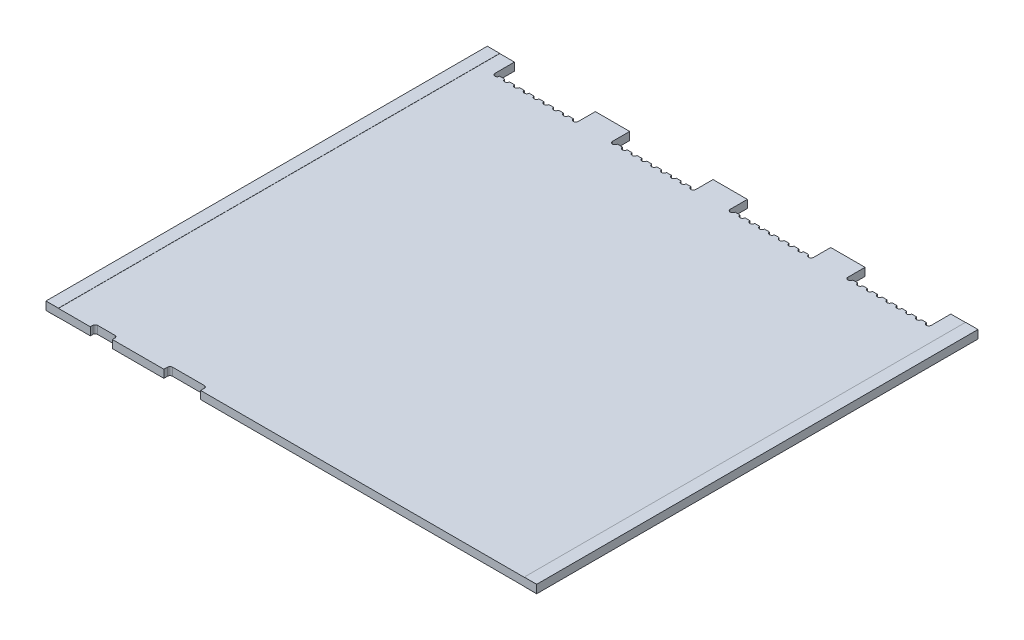
SolidWorks part; units mm, degrees
ref_plane "Front Plane" through (0, 0, 0) normal (0, 0, 1) x (1, 0, 0)
ref_plane "Top Plane" through (0, 0, 0) normal (0, 1, 0) x (1, 0, 0)
ref_plane "Right Plane" through (0, 0, 0) normal (1, 0, 0) x (0, 0, -1)
sketch "Sketch1" plane through (0, 0, 0) normal (0, 1, 0) x (1, 0, 0)
  line B0 (0, 90) -> (5.5, 90)
  line B1 (5.5, 90) -> (5.5, 86)
  line B2 (6.5, 86) -> (7.5, 86)
  line B3 (8.5, 86) -> (9.5, 86)
  line B4 (10.5, 86) -> (11.5, 86)
  line B5 (12.5, 86) -> (13.5, 86)
  line B6 (14.5, 86) -> (15.5, 86)
  line B7 (16.5, 86) -> (17.5, 86)
  line B8 (18.5, 86) -> (19.5, 86)
  line B9 (20.5, 86) -> (21.5, 86)
  line B10 (22.5, 86) -> (22.5, 89.5)
  line B11 (22.5, 89.5) -> (29.5, 89.5)
  line B12 (29.5, 89.5) -> (29.5, 86)
  line B13 (30.5, 86) -> (31.5, 86)
  line B14 (32.5, 86) -> (33.5, 86)
  line B15 (34.5, 86) -> (35.5, 86)
  line B16 (36.5, 86) -> (37.5, 86)
  line B17 (38.5, 86) -> (39.5, 86)
  line B18 (40.5, 86) -> (41.5, 86)
  line B19 (42.5, 86) -> (43.5, 86)
  line B20 (44.5, 86) -> (45.5, 86)
  line B21 (46.5, 86) -> (46.5, 89.5)
  line B22 (46.5, 89.5) -> (53.5, 89.5)
  line B23 (53.5, 89.5) -> (53.5, 86)
  line B24 (54.5, 86) -> (55.5, 86)
  line B25 (56.5, 86) -> (57.5, 86)
  line B26 (58.5, 86) -> (59.5, 86)
  line B27 (60.5, 86) -> (61.5, 86)
  line B28 (62.5, 86) -> (63.5, 86)
  line B29 (64.5, 86) -> (65.5, 86)
  line B30 (66.5, 86) -> (67.5, 86)
  line B31 (68.5, 86) -> (69.5, 86)
  line B32 (70.5, 86) -> (70.5, 89.5)
  line B33 (70.5, 89.5) -> (77.5, 89.5)
  line B34 (77.5, 89.5) -> (77.5, 86)
  line B35 (78.5, 86) -> (79.5, 86)
  line B36 (80.5, 86) -> (81.5, 86)
  line B37 (82.5, 86) -> (83.5, 86)
  line B38 (84.5, 86) -> (85.5, 86)
  line B39 (86.5, 86) -> (87.5, 86)
  line B40 (88.5, 86) -> (89.5, 86)
  line B41 (90.5, 86) -> (91.5, 86)
  line B42 (92.5, 86) -> (93.5, 86)
  line B43 (94.5, 86) -> (94.5, 90)
  line B44 (94.5, 90) -> (100, 90)
  line B45 (100, 90) -> (100, 0)
  line B46 (100, 0) -> (31.5, 0)
  line B47 (31.5, 0) -> (31.5, 0.75)
  line B48 (31, 1.25) -> (24.5, 1.25)
  line B49 (24, 0.75) -> (24, 0)
  line B50 (24, 0) -> (13.5, 0)
  line B51 (13.5, 0) -> (13.5, 0.4375)
  line B52 (13, 1) -> (9.5, 1)
  line B53 (9, 0.5) -> (9, 0)
  line B54 (9, 0) -> (0, 0)
  line B55 (0, 0) -> (0, 90)
  arc B56 (5.5, 86) -> (6.5, 86) centre (6, 86) ccw
  arc B57 (7.5, 86) -> (8.5, 86) centre (8, 86) ccw
  arc B58 (9.5, 86) -> (10.5, 86) centre (10, 86) ccw
  arc B59 (11.5, 86) -> (12.5, 86) centre (12, 86) ccw
  arc B60 (13.5, 86) -> (14.5, 86) centre (14, 86) ccw
  arc B61 (15.5, 86) -> (16.5, 86) centre (16, 86) ccw
  arc B62 (17.5, 86) -> (18.5, 86) centre (18, 86) ccw
  arc B63 (19.5, 86) -> (20.5, 86) centre (20, 86) ccw
  arc B64 (21.5, 86) -> (22.5, 86) centre (22, 86) ccw
  arc B65 (29.5, 86) -> (30.5, 86) centre (30, 86) ccw
  arc B66 (31.5, 86) -> (32.5, 86) centre (32, 86) ccw
  arc B67 (33.5, 86) -> (34.5, 86) centre (34, 86) ccw
  arc B68 (35.5, 86) -> (36.5, 86) centre (36, 86) ccw
  arc B69 (37.5, 86) -> (38.5, 86) centre (38, 86) ccw
  arc B70 (39.5, 86) -> (40.5, 86) centre (40, 86) ccw
  arc B71 (41.5, 86) -> (42.5, 86) centre (42, 86) ccw
  arc B72 (43.5, 86) -> (44.5, 86) centre (44, 86) ccw
  arc B73 (45.5, 86) -> (46.5, 86) centre (46, 86) ccw
  arc B74 (53.5, 86) -> (54.5, 86) centre (54, 86) ccw
  arc B75 (55.5, 86) -> (56.5, 86) centre (56, 86) ccw
  arc B76 (57.5, 86) -> (58.5, 86) centre (58, 86) ccw
  arc B77 (59.5, 86) -> (60.5, 86) centre (60, 86) ccw
  arc B78 (61.5, 86) -> (62.5, 86) centre (62, 86) ccw
  arc B79 (63.5, 86) -> (64.5, 86) centre (64, 86) ccw
  arc B80 (65.5, 86) -> (66.5, 86) centre (66, 86) ccw
  arc B81 (67.5, 86) -> (68.5, 86) centre (68, 86) ccw
  arc B82 (69.5, 86) -> (70.5, 86) centre (70, 86) ccw
  arc B83 (77.5, 86) -> (78.5, 86) centre (78, 86) ccw
  arc B84 (79.5, 86) -> (80.5, 86) centre (80, 86) ccw
  arc B85 (81.5, 86) -> (82.5, 86) centre (82, 86) ccw
  arc B86 (83.5, 86) -> (84.5, 86) centre (84, 86) ccw
  arc B87 (85.5, 86) -> (86.5, 86) centre (86, 86) ccw
  arc B88 (87.5, 86) -> (88.5, 86) centre (88, 86) ccw
  arc B89 (89.5, 86) -> (90.5, 86) centre (90, 86) ccw
  arc B90 (91.5, 86) -> (92.5, 86) centre (92, 86) ccw
  arc B91 (93.5, 86) -> (94.5, 86) centre (94, 86) ccw
  arc B92 (31.5, 0.75) -> (31, 1.25) centre (31, 0.75) ccw
  arc B93 (24.5, 1.25) -> (24, 0.75) centre (24.5, 0.75) ccw
  arc B94 (13.5, 0.4375) -> (13, 1) centre (13.0034, 0.4995) ccw
  arc B95 (9.5, 1) -> (9, 0.5) centre (9.5, 0.5) ccw
sketch_block_instance "BOARD_52-2"
sketch_block "BOARD_52"
extrude "FR4" add sketch "Sketch1" along normal blind 1.6154
sketch "Sketch2" plane through (0, 0, 0) normal (0, 0, 1) x (1, 0, 0)
  line L0 (0, 1.6154) -> (9, 1.6154) construction
  line L1 (2.5, 1.6154) -> (2.5, 1.651)
  line L2 (2.5, 1.651) -> (-0.0356, 1.651)
  line L3 (-0.0356, 1.651) -> (-0.0356, -0.0356)
  line L4 (-0.0356, -0.0356) -> (2.5, -0.0356)
  line L5 (2.5, -0.0356) -> (2.5, 0)
  line L6 (0, 0) -> (9, 0) construction
  line L7 (2.5, 0) -> (0, 0)
  line L8 (0, 0) -> (0, 1.6154)
  line L9 (0, 1.6154) -> (2.5, 1.6154)
  line L10 (-0.0356, 0.9975) -> (0, 0.9975) construction
  line L11 (100, 1.6154) -> (100, 0)
  line L12 (100.0356, -0.0356) -> (100.0356, 1.651)
  line L13 (100.0356, 0.6179) -> (100, 0.6179) construction
  line L14 (97.5, -0.0356) -> (100.0356, -0.0356)
  line L15 (100, 0) -> (97.5, 0)
  line L16 (100.0356, 1.651) -> (97.5, 1.651)
  line L17 (97.5, 1.6154) -> (100, 1.6154)
  line L18 (97.5, 0) -> (97.5, -0.0356)
  line L19 (97.5, 1.651) -> (97.5, 1.6154)
extrude "gold-plating" add sketch "Sketch2" against normal through all separate body
